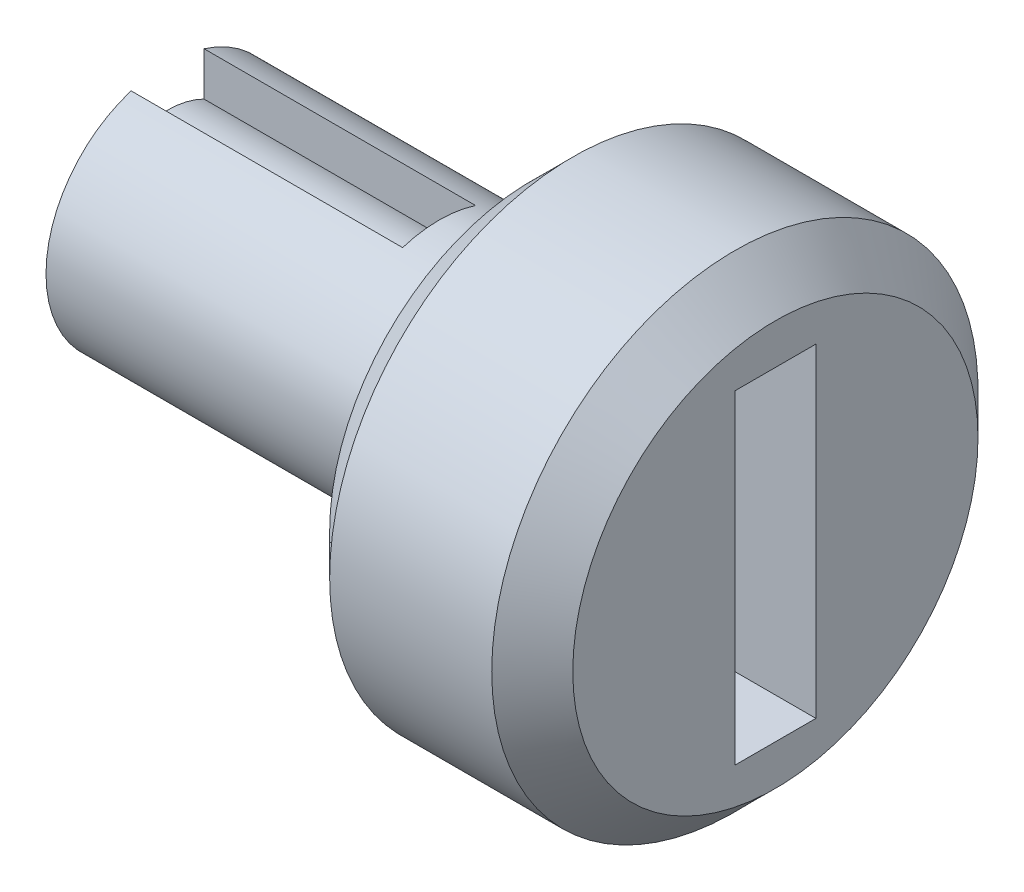
SolidWorks part; units mm, degrees
ref_plane "Front Plane" through (0, 0, 0) normal (0, 0, 1) x (1, 0, 0)
ref_plane "Top Plane" through (0, 0, 0) normal (0, 1, 0) x (1, 0, 0)
ref_plane "Right Plane" through (0, 0, 0) normal (1, 0, 0) x (0, 0, -1)
sketch "Sketch2" plane through (0, 0, 0) normal (0, 1, 0) x (1, 0, 0)
  line L0 (0, 0) -> (0, 3)
  line L1 (0, 3) -> (9, 3)
  line L2 (9, 3) -> (9, 6)
  line L3 (9, 6) -> (15, 6)
  line L4 (15, 6) -> (15, 0)
  line L5 (15, 0) -> (0, 0)
  line L6 (0, 0) -> (33.3109, 0) construction
  dimension "D1" = 15
  dimension "D2" = 6
  dimension "D3" = 6
  dimension "D4" = 12
revolve "Revolve1" add sketch "Sketch2" angle 360 about L6
sketch "Sketch3" plane through (0, 0, 0) normal (-1, 0, 0) x (0, 0, 1)
  circle A0 centre (0, 0) radius 1.2
  dimension "D1" = 2.4
extrude "Cut-Extrude1" cut sketch "Sketch3" against normal up to surface (9 mm away) up to face at (9, 0, 3)
cosmetic thread "Cosmetic Thread1" parameters "D2"=3
sketch "Sketch4" plane through (15, 0, 0) normal (1, 0, 0) x (0, 0, -1)
  line L1 (-1, -4) -> (1, -4)
  line L2 (-1, -4) -> (-1, 4)
  line L3 (-1, 4) -> (1, 4)
  line L4 (1, -4) -> (1, 4)
  line L5 (-1, -4) -> (1, 4) construction
  line L6 (-1, 4) -> (1, -4) construction
  point P0 (0, 0)
  dimension "D1" = 2
  dimension "D2" = 8
extrude "Cut-Extrude2" cut sketch "Sketch4" against normal blind 4
chamfer "Chamfer1" distance 1 angle 45 2 edges at (15, 0, 6) (9, 0, 6)
sketch "Sketch5" plane through (0, 0, 0) normal (-1, 0, 0) x (0, 0, 1)
  line L0 (-0.9, 2.3239) -> (0.9, 2.3239) construction
  line L1 (0, 2.3239) -> (0, 0) construction
  line L2 (-0.9, 2.8618) -> (-0.9, 1.7861)
  line L3 (0, 0) -> (0, -2.3239) construction
  line L4 (0.9, 2.8618) -> (0.9, 1.7861)
  line L5 (-0.9, -2.3239) -> (0.9, -2.3239) construction
  line L6 (-0.9, -1.7861) -> (-0.9, -2.8618)
  line L8 (0.9, -1.7861) -> (0.9, -2.8618)
  circle A0 centre (0, 0) radius 3 construction
  arc A1 (0.9, 2.8618) -> (-0.9, 2.8618) centre (0, 0) ccw
  arc A4 (-0.9, -2.8618) -> (0.9, -2.8618) centre (0, 0) ccw
  arc A6 (0.9, 1.7861) -> (-0.9, 1.7861) centre (0, 0) ccw
  arc A7 (-0.9, -1.7861) -> (0.9, -1.7861) centre (0, 0) ccw
  point P11 (0, -2.3239)
  dimension "D2" = 4
  dimension "D1" = 1.8
extrude "Cut-Extrude3" cut sketch "Sketch5" against normal offset from surface (6.7 mm away) 2.3 up to face at (9, 0, -5)
